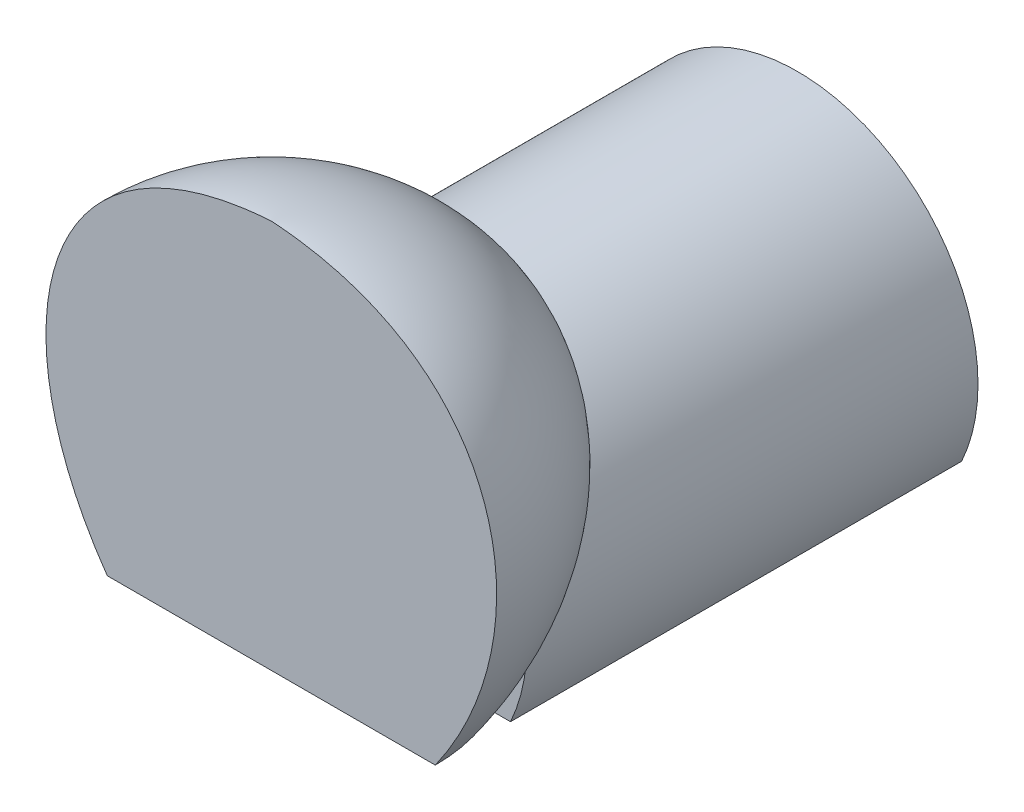
SolidWorks part; units mm, degrees
ref_plane "Front Plane" through (0, 0, 0) normal (0, 0, 1) x (1, 0, 0)
ref_plane "Top Plane" through (0, 0, 0) normal (0, 1, 0) x (1, 0, 0)
ref_plane "Right Plane" through (0, 0, 0) normal (1, 0, 0) x (0, 0, -1)
sketch "Sketch1" plane through (0, 0, 0) normal (0, 0, 1) x (1, 0, 0)
  line L0 (0, 0) -> (21.8174, 0)
  arc A0 (0, 0) -> (21.8174, 0) centre (10.9087, 5) cw
  dimension "D1" = 12
  dimension "D2" = 5
extrude "Boss-Extrude1" add sketch "Sketch1" along normal blind 30
ref_plane "Plane1" through (0, 0, 35) normal (0, 0, 1) x (1, 0, 0)
sketch "Sketch4" plane through (0, 0, 35) normal (0, 0, 1) x (1, 0, 0)
  line L0 (10.9087, 0) -> (10.9087, 25.8844)
  line L1 (0, 0) -> (21.8174, 0) construction
  line L2 (10.9087, 0) -> (21.8174, 0)
  spline S0 degree 3 poles (10.9087, 25.8844) (26.5412, 24.8624) (29.5168, 10.9151) (21.8174, 0) knots 0 0 0 0 1 1 1 1
  point P5 (10.9087, 25.8844)
revolve "Revolve1" add sketch "Sketch4" angle 180 about L0
